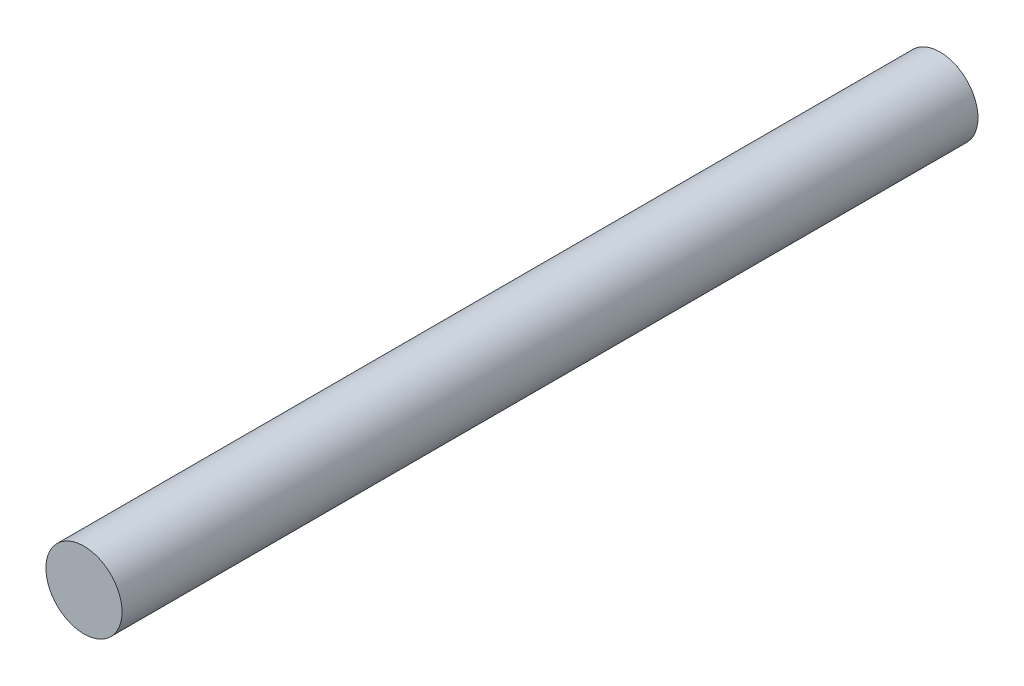
SolidWorks part; units mm, degrees
ref_plane "Plan de face" through (0, 0, 0) normal (0, 0, 1) x (1, 0, 0)
ref_plane "Plan de dessus" through (0, 0, 0) normal (0, 1, 0) x (1, 0, 0)
ref_plane "Plan de droite" through (0, 0, 0) normal (1, 0, 0) x (0, 0, -1)
sketch "Esquisse1" plane through (0, 0, 0) normal (0, 0, 1) x (1, 0, 0)
  circle A0 centre (0, 0) radius 10
  dimension "D1" = 20
extrude "Boss.-Extru.1" add sketch "Esquisse1" along normal mid plane 225
